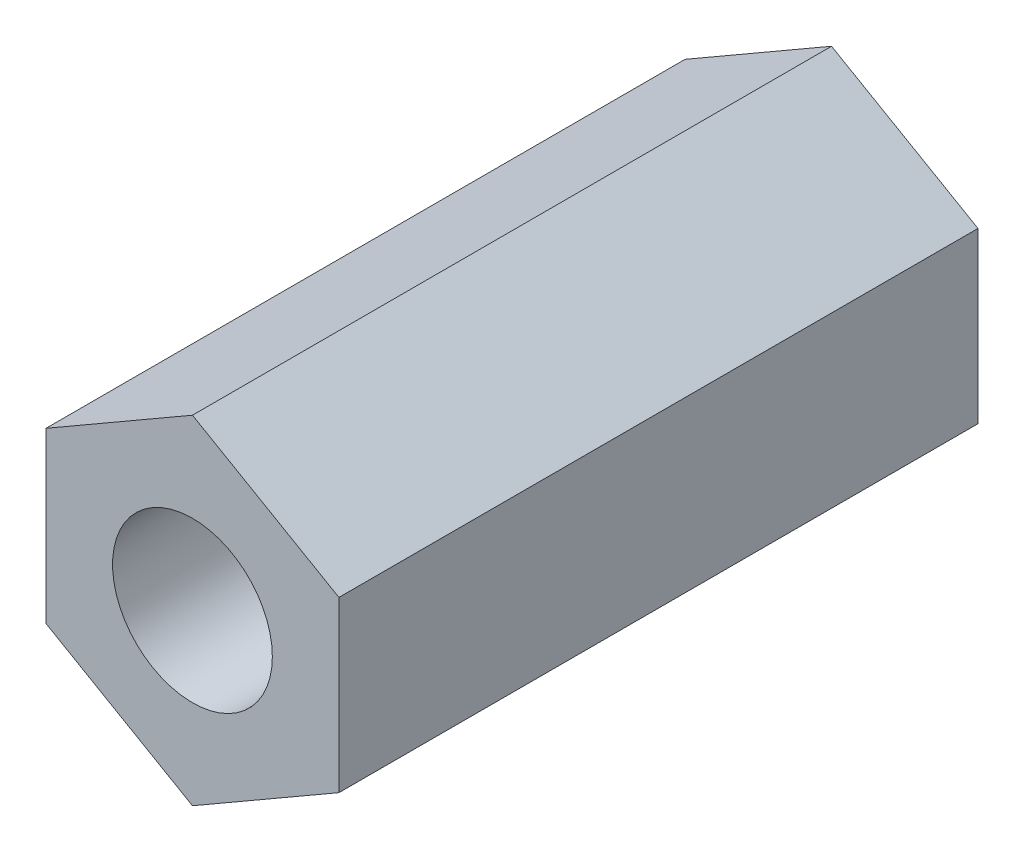
SolidWorks part; units mm, degrees
ref_plane "Front Plane" through (0, 0, 0) normal (0, 0, 1) x (1, 0, 0)
ref_plane "Top Plane" through (0, 0, 0) normal (0, 1, 0) x (1, 0, 0)
ref_plane "Right Plane" through (0, 0, 0) normal (1, 0, 0) x (0, 0, -1)
sketch "Эскиз1" plane through (0, 0, 0) normal (0, 0, 1) x (1, 0, 0)
  line L0 (-2.75, 1.5877) -> (2.75, 1.5877) construction
  line L1 (2.75, 1.5877) -> (0, 3.1754)
  line L2 (0, 3.1754) -> (-2.75, 1.5877)
  line L3 (-2.75, 1.5877) -> (-2.75, -1.5877)
  line L4 (-2.75, -1.5877) -> (0, -3.1754)
  line L5 (0, -3.1754) -> (2.75, -1.5877)
  line L6 (2.75, -1.5877) -> (2.75, 1.5877)
  circle A0 centre (0, 0) radius 2.75 construction
  circle A1 centre (0, 0) radius 1.5
  dimension "D2" = 3
  dimension "D1" = 5.5
extrude "Бобышка-Вытянуть1" add sketch "Эскиз1" along normal mid plane 12
